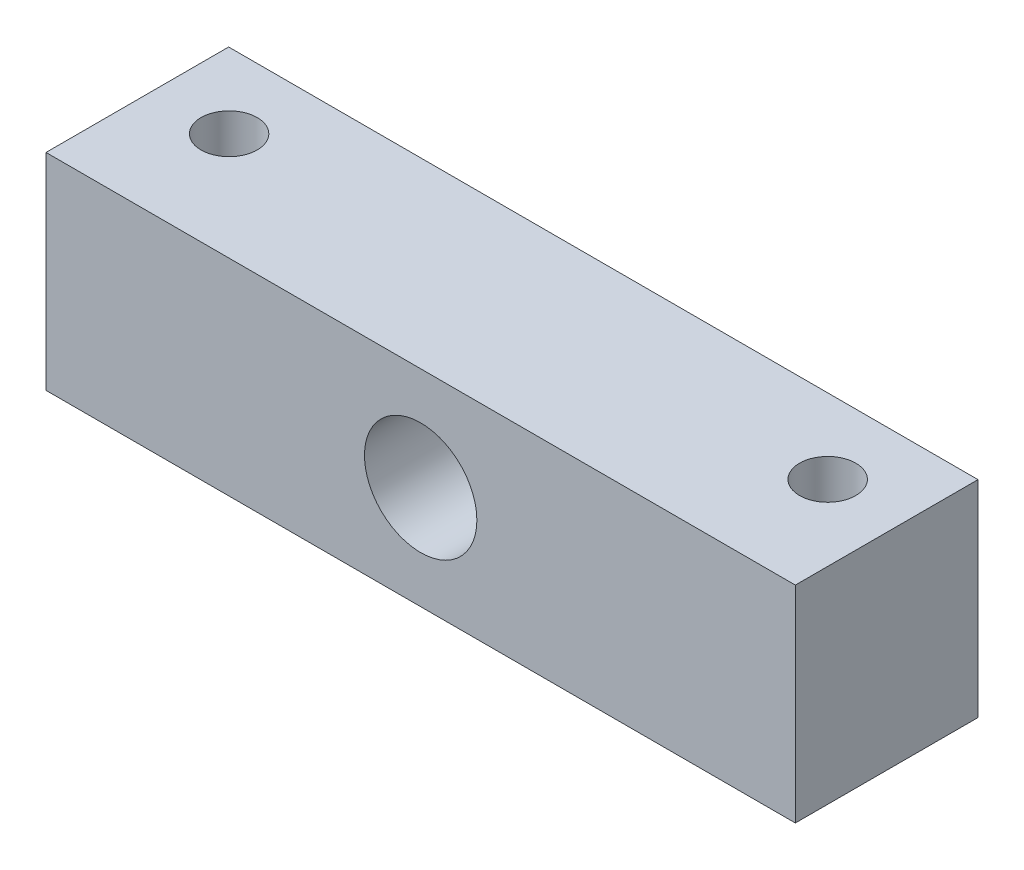
SolidWorks part; units mm, degrees
ref_plane "Front" through (0, 0, 0) normal (0, 0, 1) x (1, 0, 0)
ref_plane "Top" through (0, 0, 0) normal (0, 1, 0) x (1, 0, 0)
ref_plane "Right" through (0, 0, 0) normal (1, 0, 0) x (0, 0, -1)
sketch "Sketch1" plane through (0, 0, 0) normal (0, 1, 0) x (1, 0, 0)
  line L0 (-20, 0) -> (20, 0) construction
  line L1 (20, -4.875) -> (-20, -4.875)
  line L2 (20, -4.875) -> (20, 4.875)
  line L3 (20, 4.875) -> (-20, 4.875)
  line L4 (-20, -4.875) -> (-20, 4.875)
  line L5 (20, -4.875) -> (-20, 4.875) construction
  line L6 (20, 4.875) -> (-20, -4.875) construction
  line L7 (0, 4.875) -> (0, -4.875) construction
  circle A0 centre (-15.9761, 0.875) radius 1.5
  circle A1 centre (15.9761, 0.875) radius 1.5
  point P0 (0, 0)
  dimension "D3" = 3
  dimension "D1" = 40
  dimension "D2" = 9.75
  dimension "D4" = 16
  dimension "D5" = 4
extrude "Boss-Extrude1" add sketch "Sketch1" along normal blind 11
sketch "Sketch2" plane through (0, 0, 4.875) normal (0, 0, 1) x (1, 0, 0)
  line L0 (0, 11) -> (0, 0) construction
  line L1 (-20, 11) -> (20, 11) construction
  line L2 (-20, 0) -> (20, 0) construction
  line L3 (20, 11) -> (20, 0) construction
  circle A0 centre (0, 5.5) radius 3
  circle A1 centre (8.5966, 4.0126) radius 1.5
  circle A2 centre (-8.5966, 4.0126) radius 1.5
  point P10 (20, 5.5)
  dimension "D1" = 6
  dimension "D3" = 3
  dimension "D2" = 11.5
extrude "Cut-Extrude1" cut sketch "Sketch2" against normal up to next contours L0 A0 | A0 L0
